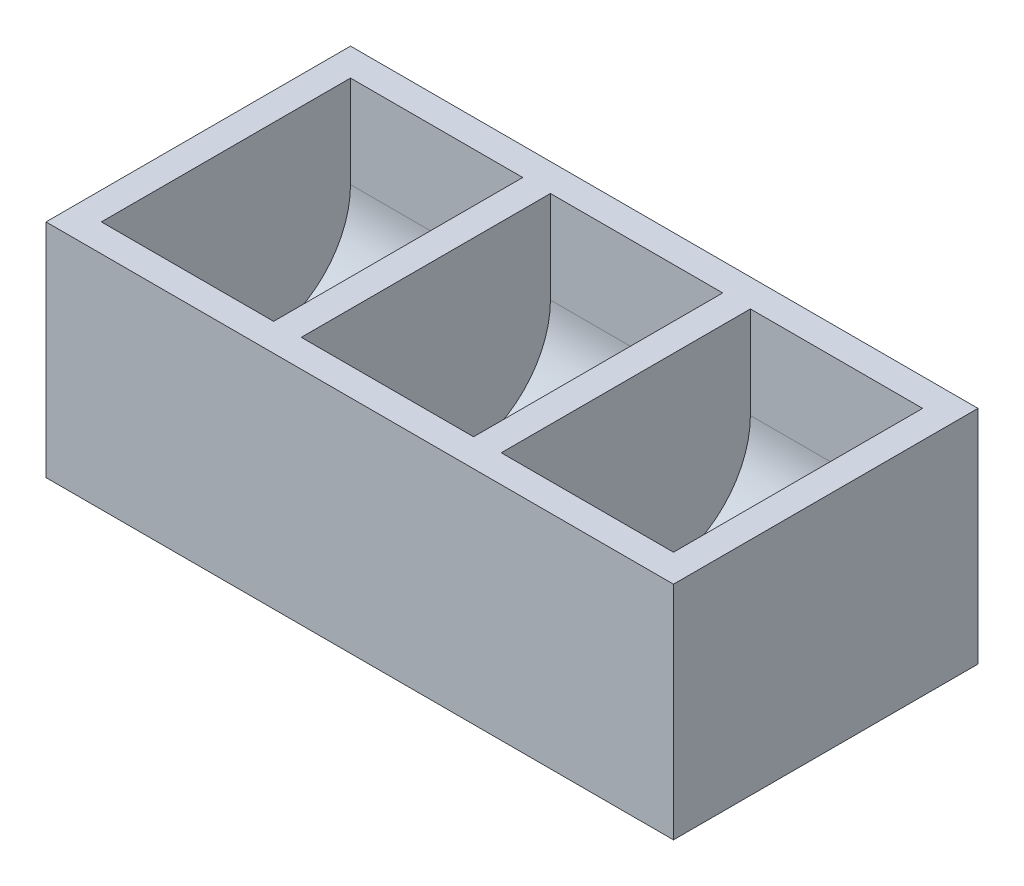
SolidWorks part; units mm, degrees
ref_plane "Front" through (0, 0, 0) normal (0, 0, 1) x (1, 0, 0)
ref_plane "Top" through (0, 0, 0) normal (0, 1, 0) x (1, 0, 0)
ref_plane "Right" through (0, 0, 0) normal (1, 0, 0) x (0, 0, -1)
sketch "Sketch1" plane through (0, 0, 0) normal (0, 1, 0) x (1, 0, 0)
  line L1 (-68, -33) -> (68, -33)
  line L2 (-68, -33) -> (-68, 33)
  line L3 (-68, 33) -> (68, 33)
  line L4 (68, -33) -> (68, 33)
  line L5 (-68, -33) -> (68, 33) construction
  line L6 (-68, 33) -> (68, -33) construction
  point P0 (0, 0)
  dimension "D1" = 136
  dimension "D2" = 66
extrude "Boss-Extrude1" add sketch "Sketch1" along normal blind 48
sketch "Sketch2" plane through (0, 48, 0) normal (0, 1, 0) x (1, 0, 0)
  line L0 (-68, 33) -> (-68, -33) construction
  line L1 (-62, -27) -> (-24.67, -27)
  line L2 (-62, -27) -> (-62, 27)
  line L3 (-62, 27) -> (-24.67, 27)
  line L4 (-24.67, -27) -> (-24.67, 27)
  line L5 (-62, -27) -> (-24.67, 27) construction
  line L6 (-62, 27) -> (-24.67, -27) construction
  line L7 (-18.67, -27) -> (18.67, -27)
  line L8 (-18.67, -27) -> (-18.67, 27)
  line L9 (-18.67, 27) -> (18.67, 27)
  line L10 (18.67, -27) -> (18.67, 27)
  line L11 (-18.67, -27) -> (18.67, 27) construction
  line L12 (-18.67, 27) -> (18.67, -27) construction
  line L13 (24.67, -27) -> (62, -27)
  line L14 (24.67, -27) -> (24.67, 27)
  line L15 (24.67, 27) -> (62, 27)
  line L16 (62, -27) -> (62, 27)
  line L17 (24.67, -27) -> (62, 27) construction
  line L18 (24.67, 27) -> (62, -27) construction
  line L19 (68, 33) -> (-68, 33) construction
  line L20 (68, -33) -> (68, 33) construction
  line L21 (-68, -33) -> (68, -33) construction
  point P0 (-43.335, 0)
  point P5 (0, 0)
  point P11 (43.335, 0)
  point P16 (-62, 0)
  dimension "D1" = 6
  dimension "D2" = 6
  dimension "D3" = 6
  dimension "D4" = 6
  dimension "D5" = 6
  dimension "D6" = 6
  dimension "D7" = 6
  dimension "D8" = 6
  dimension "D9" = 6
  dimension "D10" = 37.33
  dimension "D11" = 54
  dimension "D12" = 37.34
  dimension "D13" = 37.33
extrude "Cut-Extrude1" cut sketch "Sketch2" against normal offset from surface (48 mm away) 8 from offset 8 up to face at (0, 0, 0)
fillet "Fillet1" radius 20 6 edges at (43.335, 8, 27) (43.335, 8, -27) (0, 8, -27) (0, 8, 27) (-43.335, 8, 27) (-43.335, 8, -27)
